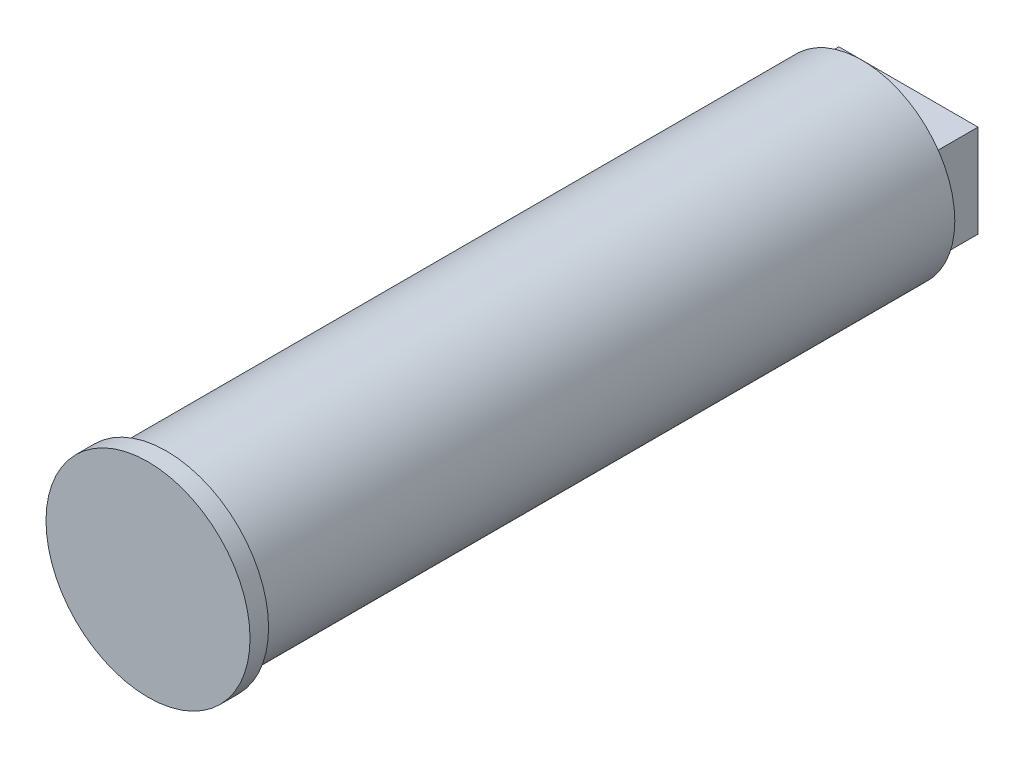
SolidWorks part; units mm, degrees
ref_plane "Alzado" through (0, 0, 0) normal (0, 0, 1) x (1, 0, 0)
ref_plane "Planta" through (0, 0, 0) normal (0, 1, 0) x (1, 0, 0)
ref_plane "Vista lateral" through (0, 0, 0) normal (1, 0, 0) x (0, 0, -1)
sketch "Croquis1" plane through (0, 0, 0) normal (0, 0, 1) x (1, 0, 0)
  circle A0 centre (0, 0) radius 10
  dimension "D1" = 20
extrude "Saliente-Extruir1" add sketch "Croquis1" along normal blind 75
sketch "Croquis2" plane through (0, 0, 75) normal (0, 0, 1) x (1, 0, 0)
  circle A0 centre (0, 0) radius 11
  dimension "D1" = 22
extrude "Saliente-Extruir2" add sketch "Croquis2" along normal blind 2
sketch "Croquis3" plane through (0, 0, 0) normal (0, 0, -1) x (-1, 0, 0)
  line L1 (7.5, 5) -> (-7.5, 5)
  line L2 (7.5, 5) -> (7.5, -5)
  line L3 (7.5, -5) -> (-7.5, -5)
  line L4 (-7.5, 5) -> (-7.5, -5)
  line L5 (7.5, 5) -> (-7.5, -5) construction
  line L6 (7.5, -5) -> (-7.5, 5) construction
  point P0 (0, 0)
  dimension "D1" = 15
  dimension "D2" = 10
extrude "Saliente-Extruir3" add sketch "Croquis3" along normal blind 5
